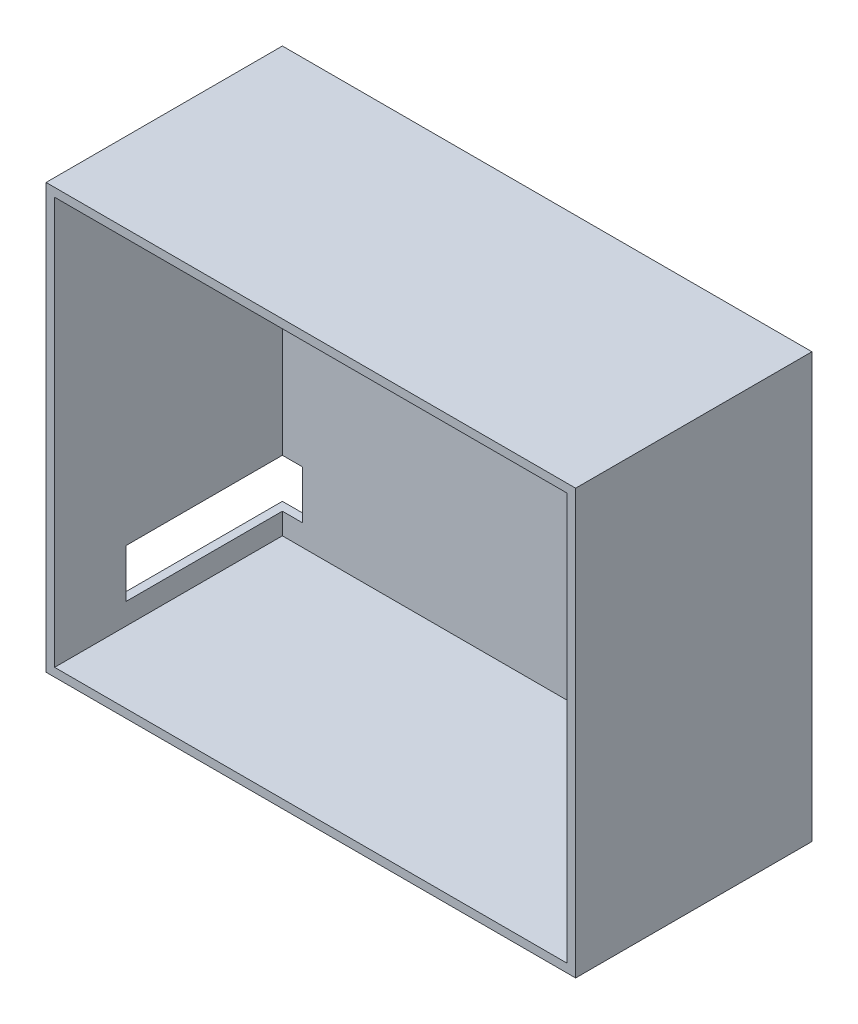
SolidWorks part; units mm, degrees
ref_plane "前视基准面" through (0, 0, 0) normal (0, 0, 1) x (1, 0, 0)
ref_plane "上视基准面" through (0, 0, 0) normal (0, 1, 0) x (1, 0, 0)
ref_plane "右视基准面" through (0, 0, 0) normal (1, 0, 0) x (0, 0, -1)
other "Configuration Table"
sketch "草图1" plane through (0, 0, 0) normal (0, 0, 1) x (1, 0, 0)
  line L1 (0, 0) -> (186, 0)
  line L2 (0, 0) -> (0, 149)
  line L3 (0, 149) -> (186, 149)
  line L4 (186, 0) -> (186, 149)
extrude "Floor_T3" add sketch "草图1" along normal blind 3
sketch "草图2" plane through (0, 0, 0) normal (0, 0, 1) x (1, 0, 0)
  line L1 (0, 0) -> (186, 0)
  line L2 (0, 0) -> (0, 149)
  line L3 (0, 149) -> (186, 149)
  line L4 (186, 0) -> (186, 149)
  line L6 (3, 3) -> (183, 3)
  line L7 (3, 3) -> (3, 146)
  line L8 (3, 146) -> (183, 146)
  line L9 (183, 3) -> (183, 146)
extrude "Walls_T3_depth80" add sketch "草图2" along normal blind 83
sketch "草图3" plane through (0, 0, 0) normal (0, 0, 1) x (1, 0, 0)
  line L1 (-1, 19.5) -> (10, 19.5)
  line L2 (-1, 19.5) -> (-1, 27.5)
  line L3 (-1, 27.5) -> (10, 27.5)
  line L4 (10, 19.5) -> (10, 27.5)
extrude "Servo_stand_relief_W8_H58" cut sketch "草图3" along normal blind 58
sketch "草图4" plane through (0, 0, 0) normal (0, 0, 1) x (1, 0, 0)
  line L1 (-1, 10.5) -> (10, 10.5)
  line L2 (-1, 10.5) -> (-1, 27.5)
  line L3 (-1, 27.5) -> (10, 27.5)
  line L4 (10, 10.5) -> (10, 27.5)
extrude "Servo_ears_relief_v3" cut sketch "草图4" along normal blind 58
